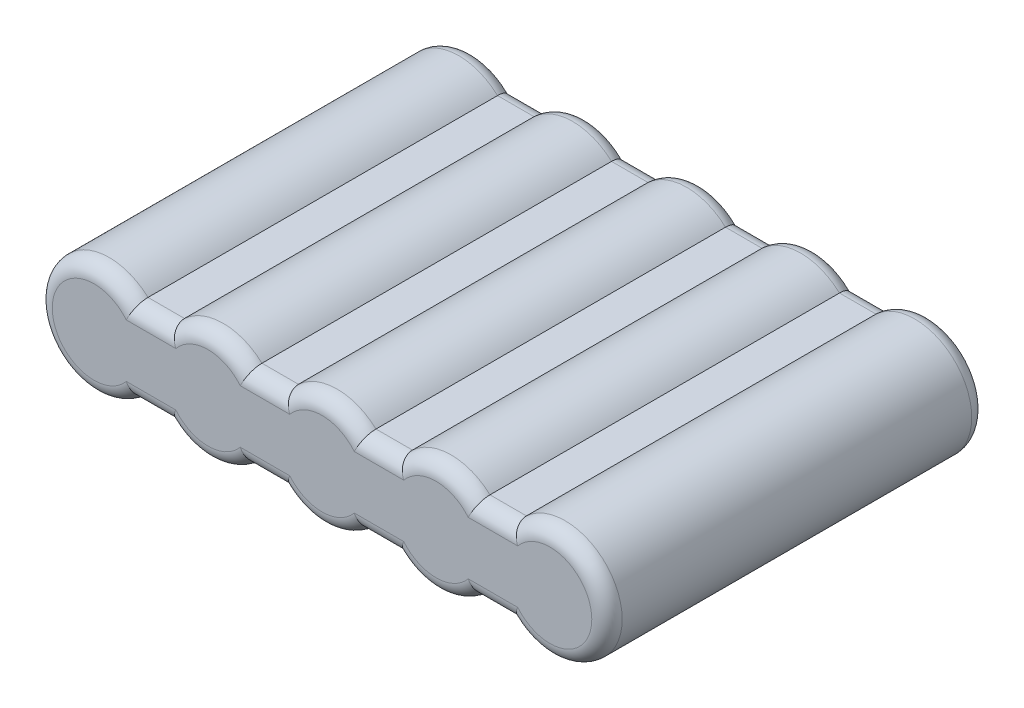
SolidWorks part; units mm, degrees
ref_plane "Front Plane" through (0, 0, 0) normal (0, 0, 1) x (1, 0, 0)
ref_plane "Top Plane" through (0, 0, 0) normal (0, 1, 0) x (1, 0, 0)
ref_plane "Right Plane" through (0, 0, 0) normal (1, 0, 0) x (0, 0, -1)
sketch "Sketch1" plane through (0, 0, 0) normal (0, 1, 0) x (1, 0, 0)
  line L1 (0, 0) -> (95.25, 0)
  line L2 (0, 0) -> (0, -63.5)
  line L3 (0, -63.5) -> (95.25, -63.5)
  line L4 (95.25, 0) -> (95.25, -63.5)
  dimension "D1" = 63.5
  dimension "D2" = 95.25
extrude "Boss-Extrude1" add sketch "Sketch1" along normal blind 19.05
sketch "Sketch2" plane through (0, 0, 63.5) normal (0, 0, 1) x (1, 0, 0)
  line L0 (0, 19.05) -> (0, 0) construction
  line L1 (95.25, 19.05) -> (95.25, 0) construction
  line L2 (16.0008, 16.51) -> (22.0992, 16.51)
  line L3 (0, 16.51) -> (0, 2.54)
  line L4 (16.0008, 2.54) -> (22.0992, 2.54)
  line L5 (95.25, 16.51) -> (95.25, 2.54)
  line L6 (0, 19.05) -> (95.25, 19.05) construction
  line L7 (0, 0) -> (95.25, 0) construction
  line L8 (35.0508, 16.51) -> (41.1492, 16.51)
  line L9 (0, 19.05) -> (95.25, 19.05)
  line L10 (0, 19.05) -> (0, 0)
  line L11 (0, 0) -> (95.25, 0)
  line L12 (95.25, 19.05) -> (95.25, 0)
  line L13 (35.0508, 2.54) -> (41.1492, 2.54)
  line L14 (54.1008, 2.54) -> (60.1992, 2.54)
  line L15 (54.1008, 16.51) -> (60.1992, 16.51)
  line L16 (73.1508, 16.51) -> (79.2492, 16.51)
  line L17 (73.1508, 2.54) -> (79.2492, 2.54)
  arc A0 (16.0008, 16.51) -> (16.0008, 2.54) centre (9.525, 9.525) ccw
  arc A1 (22.0992, 2.54) -> (35.0508, 2.54) centre (28.575, 9.525) ccw
  arc A2 (41.1492, 2.54) -> (54.1008, 2.54) centre (47.625, 9.525) ccw
  arc A3 (60.1992, 2.54) -> (73.1508, 2.54) centre (66.675, 9.525) ccw
  arc A4 (79.2492, 2.54) -> (79.2492, 16.51) centre (85.725, 9.525) ccw
  arc A5 (35.0508, 16.51) -> (22.0992, 16.51) centre (28.575, 9.525) ccw
  arc A6 (54.1008, 16.51) -> (41.1492, 16.51) centre (47.625, 9.525) ccw
  arc A7 (73.1508, 16.51) -> (60.1992, 16.51) centre (66.675, 9.525) ccw
  point P4 (0, 9.525)
  dimension "D1" = 19.05
  dimension "D2" = 19.05
  dimension "D3" = 19.05
  dimension "D4" = 19.05
  dimension "D5" = 19.05
  dimension "D6" = 2.54
  dimension "D7" = 2.54
extrude "Cut-Extrude1" cut sketch "Sketch2" against normal through all flip side to cut contours L2 A5 L8 A6 L15 A7 L16 A4 L17 A3 L14 A2 L13 A1 L4 A0
fillet "Fillet1" radius 2.54 32 edges at (19.05, 16.51, 0) (28.575, 19.05, 0) (38.1, 16.51, 0) (47.625, 19.05, 0) (57.15, 16.51, 0) (66.675, 19.05, 0) (76.2, 16.51, 0) (95.25, 9.525, 0) (76.2, 2.54, 0) (66.675, 0, 0) (57.15, 2.54, 0) (47.625, 0, 0) (38.1, 2.54, 0) (28.575, 0, 0) (19.05, 2.54, 0) (0, 9.525, 0) (19.05, 16.51, 63.5) (28.575, 19.05, 63.5) (38.1, 16.51, 63.5) (47.625, 19.05, 63.5) (57.15, 16.51, 63.5) (66.675, 19.05, 63.5) (76.2, 16.51, 63.5) (95.25, 9.525, 63.5) (76.2, 2.54, 63.5) (66.675, 0, 63.5) (57.15, 2.54, 63.5) (47.625, 0, 63.5) (38.1, 2.54, 63.5) (28.575, 0, 63.5) (19.05, 2.54, 63.5) (0, 9.525, 63.5)
